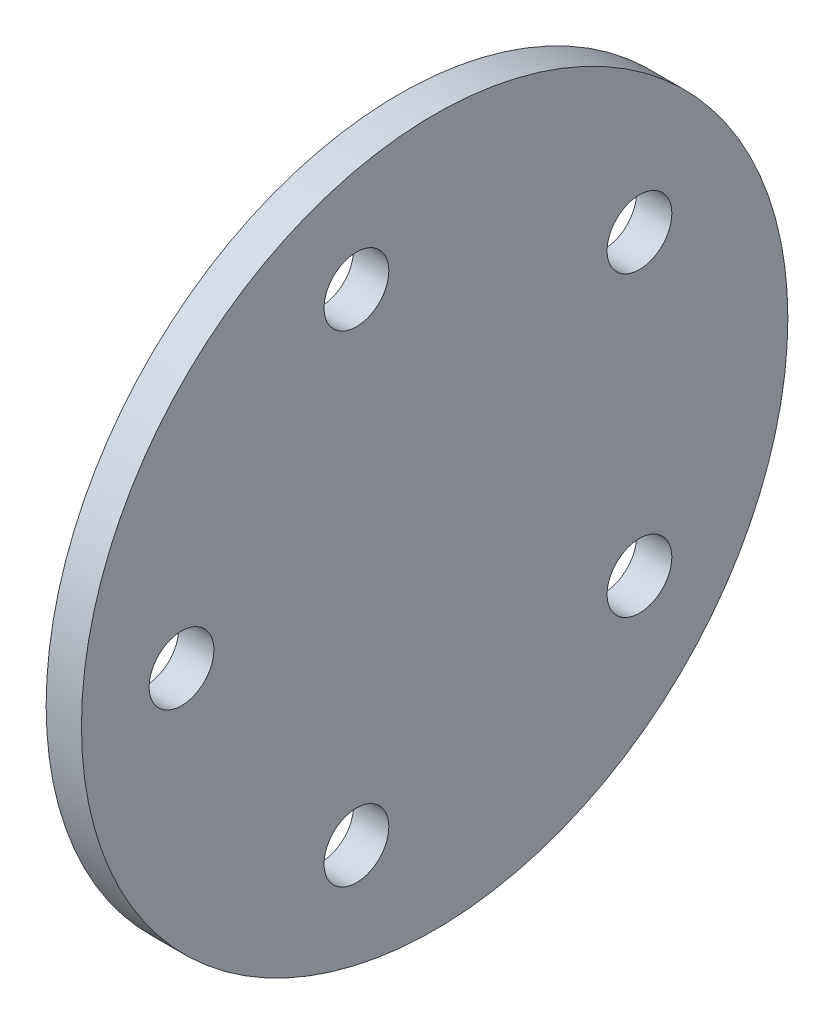
SolidWorks part; units mm, degrees
ref_plane "Front Plane" through (0, 0, 0) normal (1, 0, 0) x (0, 1, 0)
ref_plane "Top Plane" through (0, 0, 0) normal (0, 0, 1) x (0, 1, 0)
ref_plane "Right Plane" through (0, 0, 0) normal (0, 1, 0) x (-1, 0, 0)
sketch "Sketch1" plane through (0, 0, 0) normal (1, 0, 0) x (0, 1, 0)
  circle A0 centre (0, 0) radius 30
  circle A1 centre (0, 0) radius 21.5 construction
  circle A2 centre (0, 21.5) radius 2.75
  circle A5 centre (20.4477, 6.6439) radius 2.75
  circle A6 centre (12.6374, -17.3939) radius 2.75
  circle A7 centre (-12.6374, -17.3939) radius 2.75
  circle A8 centre (-20.4477, 6.6439) radius 2.75
  point P17 (0, 0)
  dimension "D1" = 60
  dimension "D2" = 43
  dimension "D3" = 5.5
  dimension "D4" = 5
extrude "Boss-Extrude1" add sketch "Sketch1" along normal blind 3
